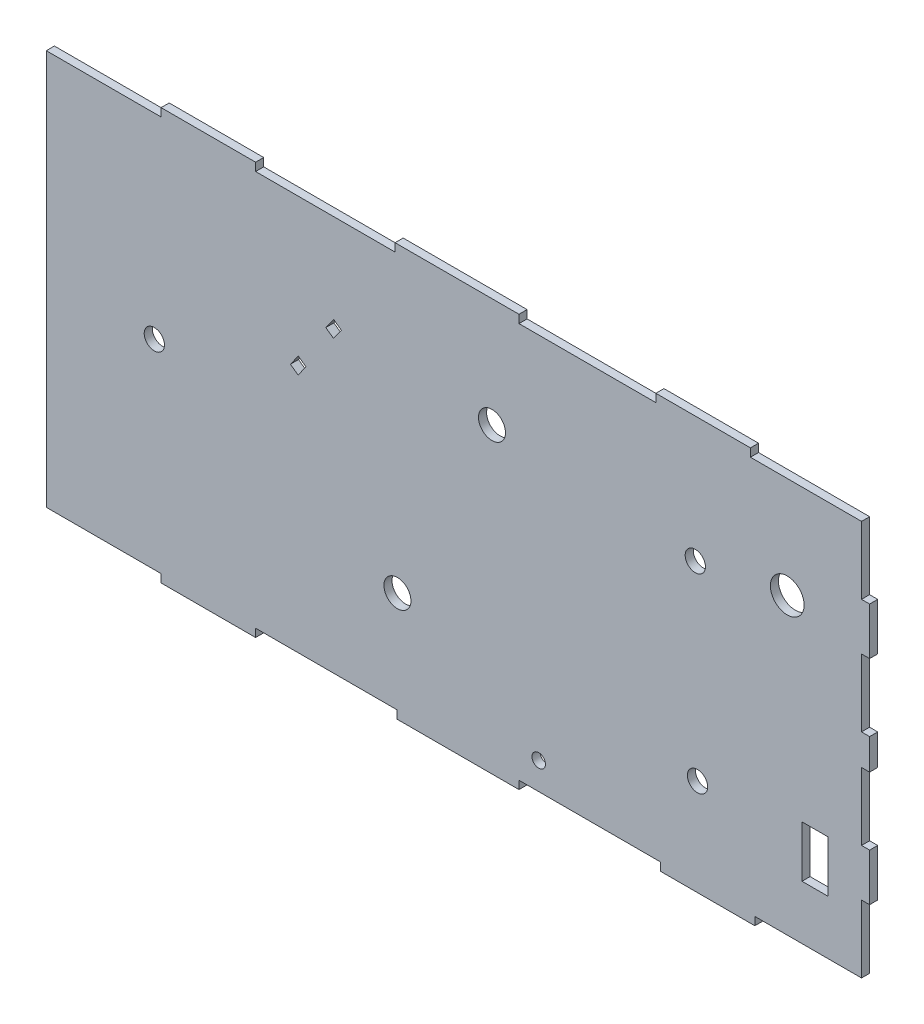
SolidWorks part; units mm, degrees
ref_plane "Front Plane" through (0, 0, 0) normal (1, 0, 0) x (0, 1, 0)
ref_plane "Top Plane" through (0, 0, 0) normal (0, 0, 1) x (0, 1, 0)
ref_plane "Right Plane" through (0, 0, 0) normal (0, 1, 0) x (-1, 0, 0)
sketch "Sketch1" plane through (0, 0, 0) normal (0, 0, 1) x (0, 1, 0)
  line L0 (302.8646, -433.0009) -> (352.8646, -433.0009)
  line L13 (352.8646, -433.0009) -> (352.8646, -439.0009)
  line L14 (387.8646, -439.0009) -> (387.8646, -433.0009)
  line L16 (302.8646, 100.5991) -> (302.8646, 170.5991)
  line L21 (387.8646, -433.0009) -> (437.8646, -433.0009)
  line L22 (302.8646, 170.5991) -> (372.8646, 170.5991)
  line L23 (525.6646, 170.5991) -> (595.6646, 170.5991)
  line L24 (595.6646, 170.5991) -> (595.6646, 100.5991)
  line L25 (437.8646, -433.0009) -> (437.8646, -439.0009)
  line L26 (575.3771, -331.0509) -> (575.3771, -375.5009) construction
  line L27 (448.4146, -375.5009) -> (575.3771, -331.0509) construction
  line L28 (460.6646, -439.0009) -> (460.6646, -433.0009)
  line L29 (448.4146, -375.5009) -> (575.3771, -375.5009) construction
  line L30 (575.3771, -375.5009) -> (575.3771, -331.0509) construction
  line L31 (460.6646, -433.0009) -> (510.6646, -433.0009)
  line L32 (510.6646, -433.0009) -> (510.6646, -439.0009)
  line L33 (545.6646, -439.0009) -> (545.6646, -433.0009)
  line L34 (545.6646, -433.0009) -> (595.6646, -433.0009)
  line L35 (387.8646, -439.0009) -> (352.8646, -439.0009)
  line L36 (460.6646, -439.0009) -> (437.8646, -439.0009)
  line L37 (448.419, -375.5134) -> (445.4651, -367.0761) construction
  line L38 (448.4146, -375.5009) -> (575.3771, -375.5009) construction
  line L39 (438.4226, -335.5242) -> (438.151, -312.2447) construction
  line L40 (429.3618, -375.7358) -> (432.1181, -367.2318) construction
  line L41 (432.1181, -367.2318) -> (368.3823, -346.5737) construction
  line L42 (480.9355, -15.8634) -> (489.0681, -21.6825)
  line L43 (525.6646, -47.8683) -> (529.7379, -42.1755)
  line L44 (445.4651, -367.0761) -> (508.7015, -344.9368) construction
  line L45 (480.9355, -15.8634) -> (485.0088, -10.1706)
  line L46 (485.0088, -10.1706) -> (493.1414, -15.9897)
  line L48 (489.0681, -21.6825) -> (493.1414, -15.9897)
  line L50 (517.532, -42.0492) -> (521.6054, -36.3564)
  line L52 (521.6054, -36.3564) -> (529.7379, -42.1755)
  line L54 (517.532, -42.0492) -> (525.6646, -47.8683)
  line L57 (342.8646, -388.9509) -> (380.9646, -388.9509)
  line L58 (342.8646, -388.9509) -> (342.8646, -408.0009)
  line L59 (342.8646, -408.0009) -> (380.9646, -408.0009)
  line L60 (380.9646, -388.9509) -> (380.9646, -408.0009)
  line L76 (372.8646, 170.5991) -> (525.6646, 170.5991)
  line L77 (595.6646, 100.5991) -> (595.6646, 85.5991)
  line L78 (595.6646, 85.5991) -> (601.6646, 85.5991)
  line L79 (601.6646, 85.5991) -> (601.6646, 15.5991)
  line L80 (601.6646, 15.5991) -> (595.6646, 15.5991)
  line L81 (595.6646, 15.5991) -> (595.6646, -87.6366)
  line L82 (595.6646, -87.6366) -> (601.6646, -87.6366)
  line L83 (601.6646, -87.6366) -> (601.6646, -179.4009)
  line L84 (601.6646, -179.4009) -> (595.6646, -179.4009)
  line L85 (595.6646, -179.4009) -> (595.6646, -280.7374)
  line L86 (595.6646, -280.7374) -> (601.6646, -280.7374)
  line L87 (601.6646, -280.7374) -> (601.6646, -350.7374)
  line L88 (601.6646, -350.7374) -> (595.6646, -350.7374)
  line L89 (595.6646, -350.7374) -> (595.6646, -433.0009)
  line L90 (545.6646, -439.0009) -> (510.6646, -439.0009)
  line L91 (302.8646, -433.0009) -> (302.8646, -354.0009)
  line L92 (302.8646, -354.0009) -> (296.8646, -354.0009)
  line L93 (296.8646, -354.0009) -> (296.8646, -284.0009)
  line L94 (296.8646, -284.0009) -> (302.8646, -284.0009)
  line L95 (302.8646, -284.0009) -> (302.8646, -179.4009)
  line L96 (302.8646, -179.4009) -> (296.8646, -179.4009)
  line L97 (296.8646, -179.4009) -> (296.8646, -89.0009)
  line L98 (296.8646, -89.0009) -> (302.8646, -89.0009)
  line L99 (302.8646, -89.0009) -> (302.8646, 15.5991)
  line L100 (302.8646, 15.5991) -> (296.8646, 15.5991)
  line L101 (296.8646, 15.5991) -> (296.8646, 85.5991)
  line L102 (296.8646, 85.5991) -> (302.8646, 85.5991)
  line L103 (302.8646, 85.5991) -> (302.8646, 100.5991)
  circle A0 centre (450.6646, 90.5991) radius 7.5
  circle A1 centre (322.8646, -194.0009) radius 5
  circle A2 centre (508.7015, -309.9368) radius 7.5
  circle A4 centre (368.3823, -311.5737) radius 7.5
  circle A5 centre (377.8646, -89.4009) radius 10
  circle A6 centre (520.6646, -159.4009) radius 10
  circle A7 centre (520.6646, -378.0009) radius 12.5
  point P29 (510.6646, -436.0009)
  point P76 (519.5687, -39.2028)
  dimension "D28" = 15
  dimension "D30" = 10
  dimension "D31" = 6
  dimension "D32" = 90
  dimension "D34" = 0
  dimension "D38" = 15
  dimension "D39" = 20
  dimension "D43" = 20
  dimension "D56" = 25
  dimension "D1" = 304.8
  dimension "D2" = 304.8
  dimension "D3" = 304.8
  dimension "D4" = 609.6
  dimension "D5" = 6
  dimension "D6" = 6
  dimension "D7" = 6
  dimension "D8" = 6
  dimension "D9" = 6
  dimension "D10" = 6
  dimension "D11" = 6
  dimension "D12" = 6
  dimension "D13" = 350
  dimension "D14" = 350
  dimension "D15" = 155
  dimension "D16" = 70
  dimension "D17" = 70
  dimension "D18" = 67
  dimension "D19" = 70
  dimension "D20" = 70
  dimension "D21" = 155
  dimension "D22" = 80
  dimension "D23" = 145
  dimension "D24" = 50
  dimension "D25" = 35
  dimension "D26" = 245
  dimension "D27" = 35
  dimension "D29" = 20
  dimension "D33" = 90
  dimension "D35" = 9.525
  dimension "D36" = 0
  dimension "D37" = 90
  dimension "D40" = 0
  dimension "D41" = 35
  dimension "D42" = 35
  dimension "D44" = 75
  dimension "D45" = 260
  dimension "D46" = 75
  dimension "D47" = 330
  dimension "D48" = 55
  dimension "D49" = 19.05
  dimension "D50" = 7
  dimension "D51" = 38.1
  dimension "D52" = 35
  dimension "D53" = 10
  dimension "D54" = 40
  dimension "D55" = 25
  dimension "D57" = 75
  dimension "D58" = 55
extrude "Boss-Extrude2" add sketch "Sketch1" along normal blind 6
sketch "Sketch5" plane through (0, 0, 0) normal (0, 0, -1) x (1, 0, 0)
  line L0 (141.102, -432.509) -> (101.9239, -485.9544)
  line L1 (101.9239, -485.9544) -> (146.0509, -518.3017)
  line L2 (146.0509, -518.3017) -> (185.229, -464.8563)
  line L4 (185.229, -464.8563) -> (141.102, -432.509)
  line L15 (87.6366, -601.6646) -> (179.4009, -601.6646)
  line L36 (-85.5991, -302.8646) -> (-100.5991, -302.8646)
  line L37 (-85.5991, -296.8646) -> (-85.5991, -302.8646)
  line L38 (-15.5991, -296.8646) -> (-85.5991, -296.8646)
  line L39 (-15.5991, -302.8646) -> (-15.5991, -296.8646)
  line L40 (89.0009, -302.8646) -> (-15.5991, -302.8646)
  line L41 (89.0009, -296.8646) -> (89.0009, -302.8646)
  line L42 (179.4009, -296.8646) -> (89.0009, -296.8646)
  line L43 (179.4009, -302.8646) -> (179.4009, -296.8646)
  line L44 (284.0009, -302.8646) -> (179.4009, -302.8646)
  line L45 (284.0009, -296.8646) -> (284.0009, -302.8646)
  line L46 (354.0009, -296.8646) -> (284.0009, -296.8646)
  line L47 (354.0009, -302.8646) -> (354.0009, -296.8646)
  line L48 (439.0009, -302.8646) -> (354.0009, -302.8646)
  line L49 (439.0009, -595.6646) -> (439.0009, -302.8646)
  line L50 (350.7374, -595.6646) -> (439.0009, -595.6646)
  line L51 (350.7374, -601.6646) -> (350.7374, -595.6646)
  line L52 (280.7374, -601.6646) -> (350.7374, -601.6646)
  line L53 (280.7374, -595.6646) -> (280.7374, -601.6646)
  line L54 (179.4009, -595.6646) -> (280.7374, -595.6646)
  line L55 (179.4009, -601.6646) -> (179.4009, -595.6646)
  line L56 (87.6366, -595.6646) -> (87.6366, -601.6646)
  line L57 (-15.5991, -595.6646) -> (87.6366, -595.6646)
  line L58 (-15.5991, -601.6646) -> (-15.5991, -595.6646)
  line L59 (-85.5991, -601.6646) -> (-15.5991, -601.6646)
  line L60 (-85.5991, -595.6646) -> (-85.5991, -601.6646)
  line L61 (-100.5991, -595.6646) -> (-85.5991, -595.6646)
  line L62 (-170.5991, -372.8646) -> (-170.5991, -525.6646)
  line L63 (-170.5991, -595.6646) -> (-100.5991, -595.6646)
  line L64 (-170.5991, -525.6646) -> (-170.5991, -595.6646)
  line L65 (-170.5991, -302.8646) -> (-170.5991, -372.8646)
  line L66 (-85.5991, -302.8646) -> (-100.5991, -302.8646)
  line L67 (-100.5991, -302.8646) -> (-170.5991, -302.8646)
  line L68 (331.0509, -575.3771) -> (331.0509, -296.8646)
  line L69 (-80.5991, -575.3771) -> (439.0009, -575.3771)
  line L70 (-80.5991, -581.3771) -> (439.0009, -581.3771)
  line L71 (-80.5991, -575.3771) -> (-80.5991, -581.3771)
  line L72 (22.0092, -350.8646) -> (27.0092, -350.8646)
  line L73 (22.0092, -350.8646) -> (22.0092, -405.8646)
  line L74 (22.0092, -405.8646) -> (27.0092, -405.8646)
  line L75 (27.0092, -350.8646) -> (27.0092, -405.8646)
  line L76 (74.4009, -367.8646) -> (79.4009, -367.8646)
  line L77 (74.4009, -367.8646) -> (74.4009, -387.8646)
  line L78 (74.4009, -387.8646) -> (79.4009, -387.8646)
  line L79 (79.4009, -367.8646) -> (79.4009, -387.8646)
  line L80 (-170.5991, -372.8646) -> (-170.5991, -391.7695)
  line L81 (-85.5991, -595.6646) -> (-170.5991, -595.6646)
  line L82 (-170.5991, -525.6646) -> (-170.5991, -509.9127)
  line L84 (433.0009, -545.6646) -> (433.0009, -595.6646) construction
  line L87 (384.4981, -429.3646) -> (390.4981, -429.3646)
  line L88 (390.4981, -429.3646) -> (409.3309, -575.3771)
  line L89 (409.3309, -575.3771) -> (403.3309, -575.3771)
  line L103 (354.0009, -296.8646) -> (284.0009, -296.8646)
  line L105 (367.0637, -432.2787) -> (347.2375, -375.649) construction
  line L106 (335.5185, -438.8896) -> (312.2375, -438.8896) construction
  line L107 (367.0637, -445.5005) -> (347.2375, -502.1302) construction
  line L108 (394.3337, -555.835) -> (394.3337, -595.6646) construction
  line L109 (390.5009, -414.6152) -> (390.5009, -595.6646) construction
  line L110 (409.3337, -595.6646) -> (409.3337, -454.6006) construction
  line L111 (257.2224, -575.3771) -> (439.0009, -575.3771) construction
  line L112 (257.2224, -581.3771) -> (439.0009, -581.3771) construction
  line L113 (375.5009, -302.8646) -> (375.5009, -595.6646) construction
  line L114 (331.0509, -296.8646) -> (331.0509, -601.6646) construction
  line L115 (284.0009, -296.8646) -> (284.0009, -302.8646)
  line L116 (354.0009, -302.8646) -> (354.0009, -296.8646)
  line L117 (439.0009, -302.8646) -> (354.0009, -302.8646)
  line L118 (439.0009, -595.6646) -> (439.0009, -302.8646)
  line L119 (350.7374, -595.6646) -> (439.0009, -595.6646)
  line L120 (350.7374, -601.6646) -> (350.7374, -595.6646)
  line L121 (280.7374, -601.6646) -> (350.7374, -601.6646)
  line L122 (280.7374, -595.6646) -> (280.7374, -601.6646)
  line L123 (384.4981, -429.3646) -> (369.4981, -429.3646)
  line L124 (394.3337, -575.3771) -> (375.5009, -448.4146)
  line L125 (384.4981, -429.3646) -> (403.3309, -575.3771)
  line L126 (375.5009, -575.3771) -> (331.0509, -575.3771)
  line L127 (375.5009, -448.4146) -> (375.5009, -575.3771)
  line L128 (369.4981, -429.3646) -> (325.0481, -302.8646)
  line L129 (375.5009, -448.4146) -> (331.0509, -575.3771)
  circle A2 centre (39.4009, -362.8646) radius 10
  circle A3 centre (39.4009, -392.8646) radius 10
  circle A4 centre (-0.5991, -482.0642) radius 10
  arc A5 (-86.5991, -302.8646) -> (5.4009, -302.8646) centre (-40.5991, -302.8646) ccw
  arc A6 (-80.5991, -302.8646) -> (-0.5991, -302.8646) centre (-40.5991, -302.8646) ccw
  circle A8 centre (129.0009, -312.8646) radius 7.5
  circle A9 centre (226.0509, -515.3771) radius 7.5
  circle A10 centre (29.4009, -522.0642) radius 10
  circle A12 centre (312.2375, -375.649) radius 7.5
  circle A13 centre (312.2375, -502.1302) radius 7.5
  arc A14 (-100.5991, -302.8646) -> (-170.5991, -372.8646) centre (-100.5991, -372.8646) ccw
  arc A15 (-100.5991, -595.6646) -> (-170.5991, -525.6646) centre (-100.5991, -525.6646) cw
  point P16 (74.4009, -377.8646)
  point P18 (24.5092, -350.8646)
  dimension "D26" = 6
  dimension "D6" = 20
  dimension "D7" = 20
  dimension "D15" = 12
  dimension "D17" = 20
  dimension "D18" = 20
  dimension "D3" = 70
  dimension "D23" = 70
  dimension "D1" = 54.7132
  dimension "D4" = 80
  dimension "D5" = 80
  dimension "D8" = 30
  dimension "D9" = 55
  dimension "D10" = 5
  dimension "D11" = 20
  dimension "D12" = 5
  dimension "D13" = 35
  dimension "D14" = 15
  dimension "D16" = 60
  dimension "D19" = 40
  dimension "D20" = 30
  dimension "D21" = 200
  dimension "D22" = 90
  dimension "D24" = 29.67
  dimension "D25" = 70
